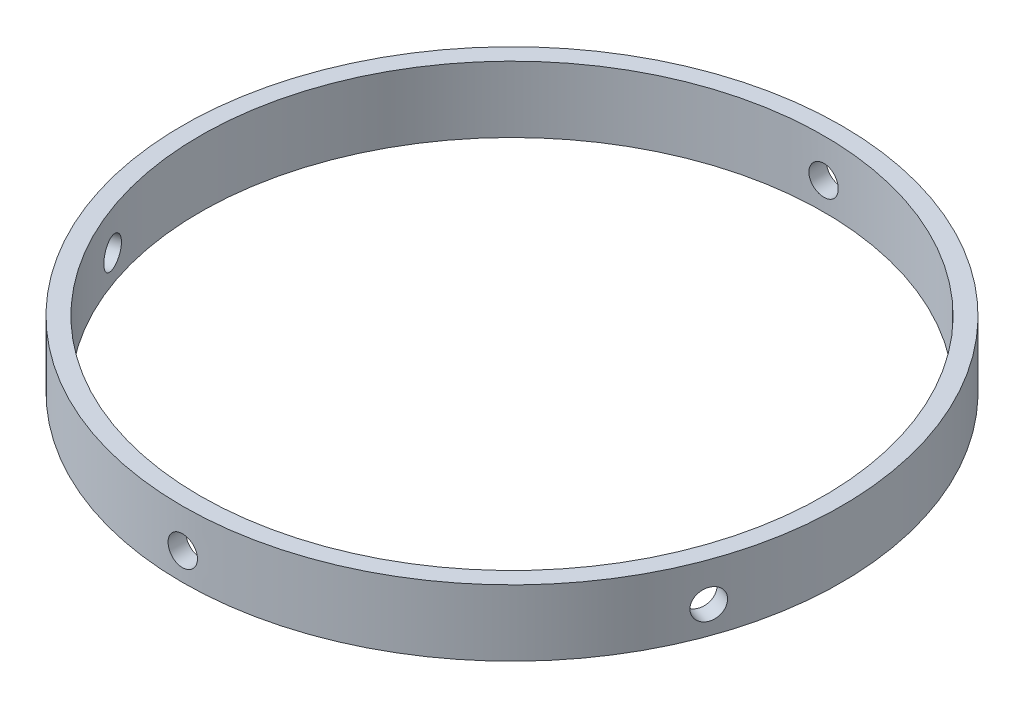
SolidWorks part; units mm, degrees
ref_plane "Front Plane" through (0, 0, 0) normal (0, 0, 1) x (1, 0, 0)
ref_plane "Top Plane" through (0, 0, 0) normal (0, 1, 0) x (1, 0, 0)
ref_plane "Right Plane" through (0, 0, 0) normal (1, 0, 0) x (0, 0, -1)
sketch "Sketch1" plane through (0, 0, 0) normal (0, 1, 0) x (1, 0, 0)
  circle A4 centre (0, 0) radius 35.941
  circle A6 centre (0, 0) radius 37.973
extrude "Boss-Extrude1" add sketch "Sketch1" along normal blind 7.62
sketch "Sketch2" plane through (0, 0, 0) normal (0, 0, 1) x (1, 0, 0)
  circle A0 centre (0, 3.171) radius 1.6929
extrude "Cut-Extrude1" cut sketch "Sketch2" along normal blind 86.62
pattern_circular "CirPattern1" count 2 over 360 about axis through (0, 3.171, 0) along (0, 0, 1) of "Cut-Extrude1"
pattern_circular "CirPattern2" count 2 every 70 about axis through (0, 7.62, 0) along (0, 1, 0) of "Cut-Extrude1"
